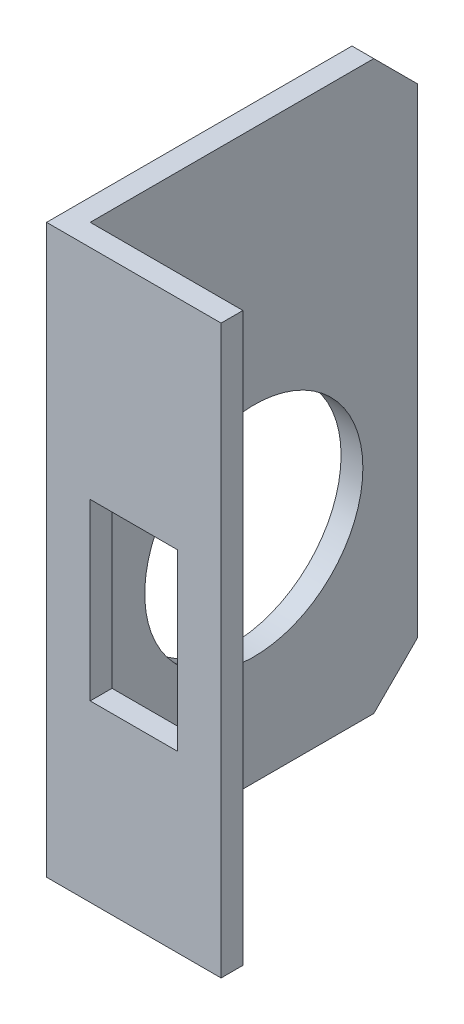
SolidWorks part; units mm, degrees
material "6061-T6 (SS)"
ref_plane "Front Plane" through (0, 0, 0) normal (0, 0, 1) x (1, 0, 0)
ref_plane "Top Plane" through (0, 0, 0) normal (0, 1, 0) x (1, 0, 0)
ref_plane "Right Plane" through (0, 0, 0) normal (1, 0, 0) x (0, 0, -1)
sketch "Sketch1" plane through (0, 0, 0) normal (0, 1, 0) x (1, 0, 0)
  line L1 (12.7, 1.5875) -> (-12.7, 1.5875)
  line L2 (12.7, 1.5875) -> (12.7, -1.5875)
  line L3 (12.7, -1.5875) -> (-12.7, -1.5875)
  line L4 (-12.7, 1.5875) -> (-12.7, -1.5875)
  line L5 (12.7, 1.5875) -> (-12.7, -1.5875) construction
  line L6 (12.7, -1.5875) -> (-12.7, 1.5875) construction
  line L7 (-9.525, 49.2125) -> (-12.7, 49.2125)
  line L8 (-9.525, 49.2125) -> (-9.525, -1.5875)
  line L9 (-9.525, -1.5875) -> (-12.7, -1.5875)
  line L10 (-12.7, 49.2125) -> (-12.7, -1.5875)
  line L11 (-9.525, 49.2125) -> (-12.7, -1.5875) construction
  line L12 (-9.525, -1.5875) -> (-12.7, 49.2125) construction
  point P0 (0, 0)
  point P6 (-11.1125, 23.8125)
  dimension "D1" = 50.8
  dimension "D2" = 3.175
  dimension "D3" = 3.175
  dimension "D4" = 25.4
extrude "Boss-Extrude1" add sketch "Sketch1" along normal blind 44.45 and the other way blind 38.1 contours L1 L8 L3 L2 | L7 L10 L1 L8 | L8 L1 L4 L3
sketch "Sketch2" plane through (-9.525, 0, 0) normal (1, 0, 0) x (0, 0, -1)
  line L0 (49.2125, -38.1) -> (1.5875, -38.1) construction
  line L1 (49.2125, 38.1) -> (42.8625, 44.45)
  line L2 (49.2125, 44.45) -> (49.2125, -38.1) construction
  line L3 (49.2125, 44.45) -> (1.5875, 44.45) construction
  line L4 (42.8625, 44.45) -> (49.2125, 44.45)
  line L5 (49.2125, 44.45) -> (49.2125, 38.1)
  line L6 (42.8625, -38.1) -> (49.2125, -38.1)
  line L7 (49.2125, -38.1) -> (49.2125, -31.75)
  line L8 (49.2125, -31.75) -> (42.8625, -38.1)
  circle A0 centre (25.4, -6.35) radius 15.875
  dimension "D1" = 31.75
  dimension "D2" = 25.4
  dimension "D3" = 31.75
  dimension "D4" = 6.35
  dimension "D5" = 6.35
  dimension "D6" = 6.35
  dimension "D7" = 6.35
extrude "Cut-Extrude1" cut sketch "Sketch2" against normal up to surface (3.175 mm away) up to face at (-12.7, 3.175, -23.8125)
sketch "Sketch3" plane through (0, 0, 1.5875) normal (0, 0, 1) x (1, 0, 0)
  line L1 (6.35, 12.7) -> (-6.35, 12.7)
  line L2 (6.35, 12.7) -> (6.35, -12.7)
  line L3 (6.35, -12.7) -> (-6.35, -12.7)
  line L4 (-6.35, 12.7) -> (-6.35, -12.7)
  line L5 (6.35, 12.7) -> (-6.35, -12.7) construction
  line L6 (6.35, -12.7) -> (-6.35, 12.7) construction
  point P0 (0, 0)
  dimension "D1" = 25.4
  dimension "D2" = 12.7
extrude "Cut-Extrude2" cut sketch "Sketch3" against normal up to surface (3.175 mm away) up to face at (1.5875, 3.175, -1.5875)
